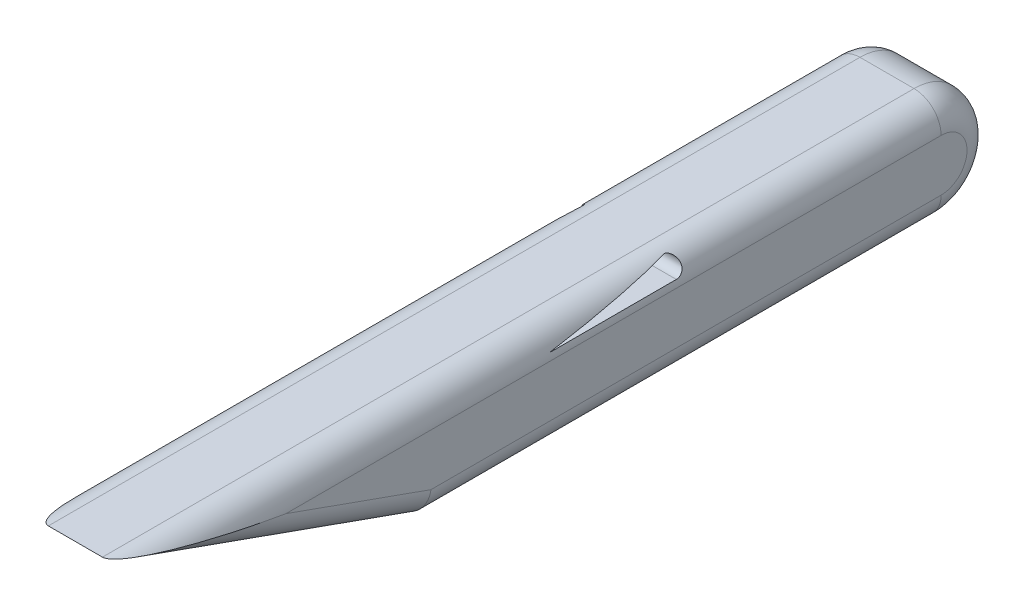
SolidWorks part; units mm, degrees
ref_plane "Front Plane" through (0, 0, 0) normal (0, 0, 1) x (1, 0, 0)
ref_plane "Top Plane" through (0, 0, 0) normal (0, 1, 0) x (1, 0, 0)
ref_plane "Right Plane" through (0, 0, 0) normal (1, 0, 0) x (0, 0, -1)
sketch "Sketch1" plane through (0, 0, 0) normal (1, 0, 0) x (0, 0, -1)
  line L0 (-537.0166, 60.4972) -> (11.6022, -135.0829)
  line L1 (11.6022, -135.0829) -> (962.9834, -135.0829)
  line L2 (-537.0166, 60.4972) -> (962.9834, 60.4972)
  arc A0 (962.9834, 60.4972) -> (962.9834, -135.0829) centre (962.9834, -37.2928) cw
  dimension "D1" = 1500
extrude "Boss-Extrude1" add sketch "Sketch1" against normal mid plane 200 contours A0 L1 L0 L2
fillet "Fillet1" radius 50 8 edges at (-100, -135.0829, -487.2928) (-100, -37.2928, -1060.7735) (100, 60.4972, -212.9834) (100, -37.2928, -1060.7735) (100, -37.2928, 262.7072) (-100, -37.2928, 262.7072) (-100, 60.4972, -212.9834) (100, -135.0829, -487.2928)
sketch "Sketch2" plane through (-100, 0, 0) normal (-1, 0, 0) x (0, 0, 1)
  line L0 (-240.2784, 23.0751) -> (-475.2168, 23.0751) construction
  line L1 (-473.2935, 53.0751) -> (-240.2784, 23.0751) construction
  line L2 (-240.2784, 23.0751) -> (-475.2168, 23.0751)
  line L3 (-473.2935, 53.0751) -> (-240.2784, 23.0751)
  arc A0 (-473.2935, 53.0751) -> (-475.2168, 23.0751) centre (-475.2168, 38.1367) ccw construction
  arc A1 (-473.2935, 53.0751) -> (-475.2168, 23.0751) centre (-475.2168, 38.1367) ccw
extrude "Cut-Extrude1" cut sketch "Sketch2" against normal blind 300
